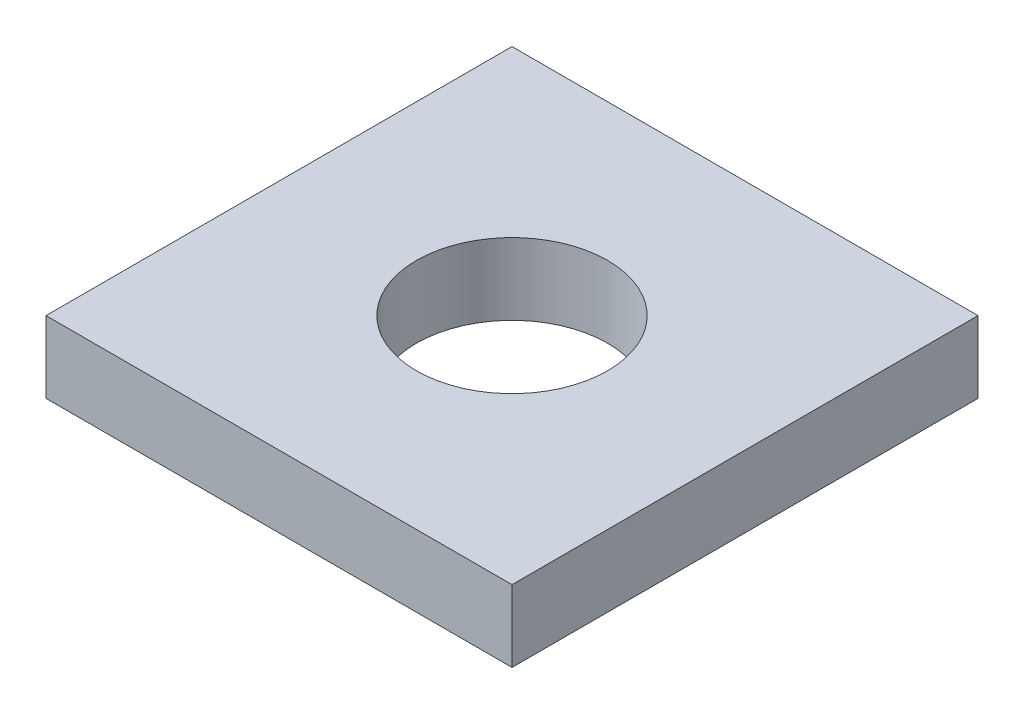
SolidWorks part; units mm, degrees
ref_plane "Front" through (0, 0, 0) normal (0, 0, 1) x (1, 0, 0)
ref_plane "Top" through (0, 0, 0) normal (0, 1, 0) x (1, 0, 0)
ref_plane "Right" through (0, 0, 0) normal (1, 0, 0) x (0, 0, -1)
sketch "Sketch1" plane through (0, 0, 0) normal (0, 1, 0) x (1, 0, 0)
  line L1 (0, 0) -> (9.75, 0)
  line L2 (0, 0) -> (0, 9.75)
  line L3 (0, 9.75) -> (9.75, 9.75)
  line L4 (9.75, 0) -> (9.75, 9.75)
  circle A0 centre (4.875, 4.875) radius 2
  dimension "D1" = 9.75
  dimension "D2" = 4.875
  dimension "D3" = 4.875
extrude "Boss-Extrude2" add sketch "Sketch1" along normal blind 1.5
equation "\"D2@Sketch1\"= \"D1@Sketch1\" / 2"
equation "\"D3@Sketch1\"=\"D1@Sketch1\" / 2"
